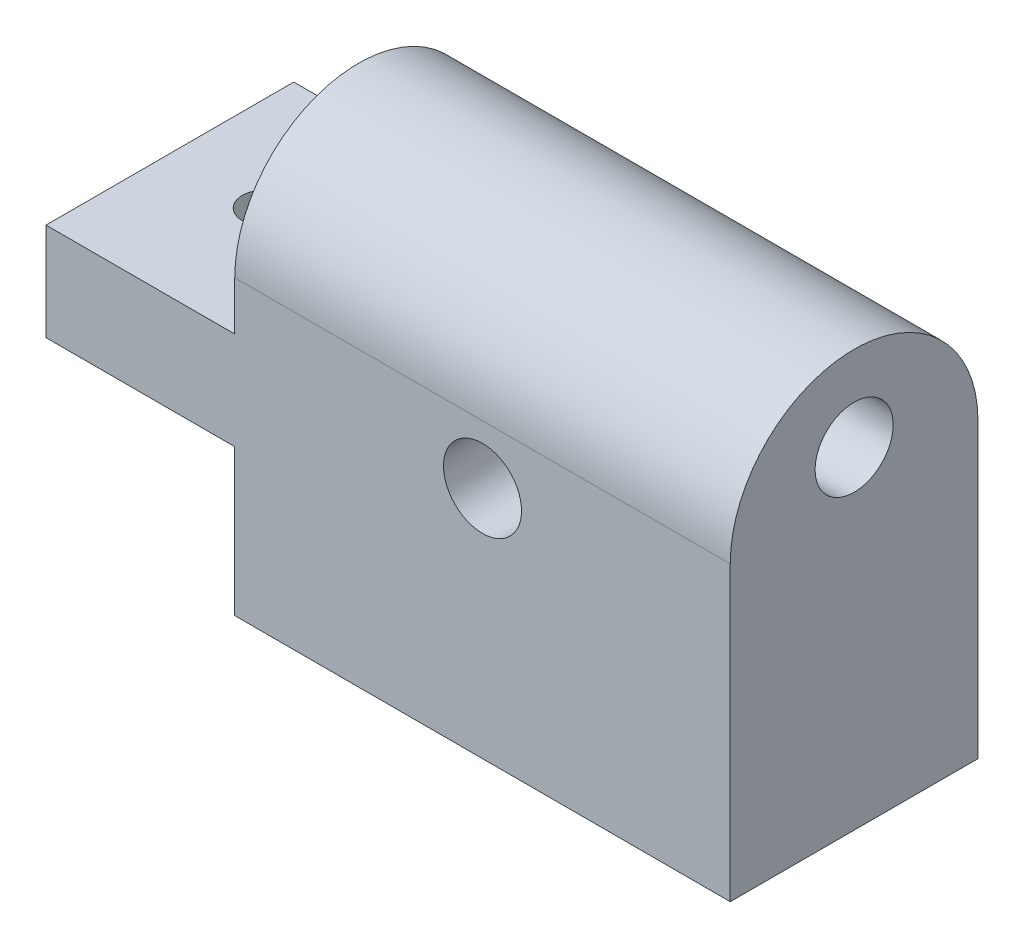
SolidWorks part; units mm, degrees
ref_plane "Front Plane" through (0, 0, 0) normal (0, 0, 1) x (1, 0, 0)
ref_plane "Top Plane" through (0, 0, 0) normal (0, 1, 0) x (1, 0, 0)
ref_plane "Right Plane" through (0, 0, 0) normal (1, 0, 0) x (0, 0, -1)
sketch "Sketch1" plane through (0, 0, 0) normal (0, 0, 1) x (1, 0, 0)
  line L0 (-25.4, -24) -> (25.4, -24)
  line L1 (25.4, -24) -> (25.4, 6)
  line L2 (25.4, 6) -> (-25.4, 6)
  line L3 (-25.4, 6) -> (-25.4, -24)
  line L4 (-25.4, -4) -> (25.4, -4) construction
  circle A0 centre (0, 0) radius 4
  point P10 (0, -24)
  dimension "D1" = 8
  dimension "D2" = 50.8
  dimension "D3" = 20
  dimension "D4" = 10
extrude "Boss-Extrude1" add sketch "Sketch1" along normal blind 25.4
sketch "Sketch2" plane through (25.4, 0, 0) normal (1, 0, 0) x (0, 0, -1)
  line L0 (-25.4, 6) -> (0, 6) construction
  line L2 (-25.4, 6) -> (-25.4, 5)
  line L3 (-25.4, 5) -> (0, 5)
  line L4 (0, -24) -> (0, 6) construction
  line L5 (0, 5) -> (0, 6)
  circle A0 centre (-12.7, 10) radius 4
  arc A1 (0, 6) -> (-25.4, 6) centre (-12.7, 6) ccw
  point P5 (-12.7, 6)
  dimension "D1" = 8
  dimension "D2" = 1
extrude "Boss-Extrude3" add sketch "Sketch2" against normal through all
sketch "Sketch4" plane through (-25.4, 0, 0) normal (-1, 0, 0) x (0, 0, 1)
  line L0 (0, 6) -> (0, -24) construction
  line L1 (25.4, -9) -> (0, -9)
  line L2 (25.4, -9) -> (25.4, 1)
  line L3 (25.4, 1) -> (0, 1)
  line L4 (0, -9) -> (0, 1)
  line L5 (25.4, -9) -> (0, 1) construction
  line L6 (25.4, 1) -> (0, -9) construction
  line L7 (25.4, 6) -> (25.4, -24) construction
  line L16 (25.4, -24) -> (0, -24) construction
  point P0 (12.7, -4)
  dimension "D2" = 10
  dimension "D3" = 15
extrude "Boss-Extrude4" add sketch "Sketch4" along normal blind 19.35
sketch "Sketch5" plane through (0, -9, 0) normal (0, -1, 0) x (1, 0, 0)
  line L0 (-44.75, 0) -> (-44.75, 25.4) construction
  line L1 (-44.75, 0) -> (-25.4, 0) construction
  circle A0 centre (-35.075, 12.7) radius 2 construction
  point P4 (-44.75, 12.7)
  point P8 (-35.075, 0)
  dimension "D1" = 4
hole_wizard "M4 Clearance Hole1" positions "Sketch6" profile "Sketch7" hole size "M4" standard "ANSI Metric" end condition through all
sketch "Sketch6" plane through (0, -9, 0) normal (0, -1, 0) x (-1, 0, 0)
  point P0 (35.075, -12.7)
sketch "Sketch7" plane through (-35.075, -9, 12.7) normal (1, 0, 0) x (0, 0, -1)
  line L0 (0, 0) -> (0, 27.7)
  line L1 (0, 27.7) -> (2.25, 27.7)
  line L2 (2.25, 27.7) -> (2.25, 0)
  line L5 (2.25, 0) -> (0, 0)
  line L11 (0, -6.35) -> (0, 107.95) construction
  dimension "Thru Hole Dia." = 4.5
  dimension "Thru Hole Depth" = 27.7
